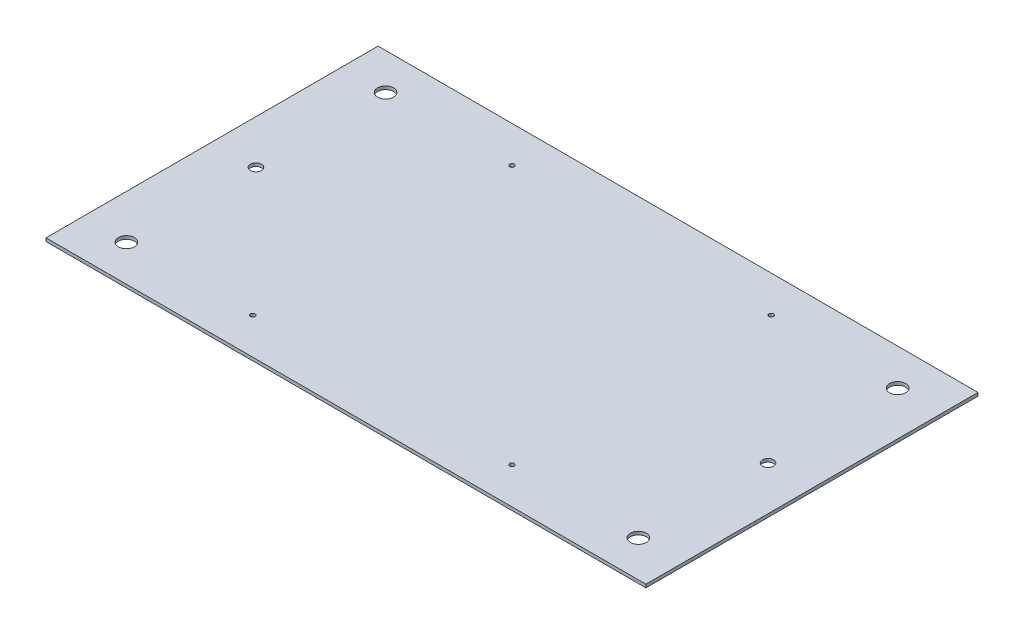
SolidWorks part; units mm, degrees
ref_plane "Front Plane" through (0, 0, 0) normal (0, 0, 1) x (1, 0, 0)
ref_plane "Top Plane" through (0, 0, 0) normal (0, 1, 0) x (1, 0, 0)
ref_plane "Right Plane" through (0, 0, 0) normal (1, 0, 0) x (0, 0, -1)
sketch "Sketch2" plane through (0, 0, 0) normal (0, 1, 0) x (1, 0, 0)
  line L1 (0, 0) -> (560, 0)
  line L2 (0, 0) -> (0, 310)
  line L3 (0, 310) -> (560, 310)
  line L4 (560, 0) -> (560, 310)
  line L5 (0, 0) -> (560, 310) construction
  line L6 (0, 310) -> (560, 0) construction
  point P4 (280, 155)
  dimension "D1" = 310
  dimension "D2" = 560
extrude "Boss-Extrude1" add sketch "Sketch2" along normal blind 3
sketch "Sketch3" plane through (0, 3, 0) normal (0, 1, 0) x (1, 0, 0)
  circle A0 centre (159, 276) radius 2.15
  circle A1 centre (401, 276) radius 2.15
  circle A2 centre (401, 34) radius 2.15
  circle A3 centre (159, 34) radius 2.15
  dimension "D1" = 4.3
  dimension "D2" = 4.3
  dimension "D3" = 4.3
  dimension "D4" = 4.3
extrude "Cut-Extrude1" cut sketch "Sketch3" against normal through all
sketch "Sketch4" plane through (0, 3, 0) normal (0, 1, 0) x (1, 0, 0)
  line L0 (0, 0) -> (560, 0) construction
  circle A0 centre (41, 155) radius 5.15
  circle A1 centre (519, 155) radius 5.15
  circle A2 centre (159, 34) radius 2.15 construction
  circle A3 centre (401, 34) radius 2.15 construction
  dimension "D1" = 118
  dimension "D2" = 118
  dimension "D3" = 155
  dimension "D4" = 155
  dimension "D5" = 10.3
  dimension "D6" = 10.3
extrude "Cut-Extrude2" cut sketch "Sketch4" against normal through all
sketch "Sketch5" plane through (0, 3, 0) normal (0, 1, 0) x (1, 0, 0)
  line L0 (0, 34) -> (560, 34) construction
  line L1 (0, 310) -> (0, 0) construction
  line L2 (560, 0) -> (560, 310) construction
  line L3 (0, 276) -> (560, 276) construction
  line L4 (41, 0) -> (41, 310) construction
  line L5 (560, 310) -> (0, 310) construction
  line L6 (519, 0) -> (519, 310) construction
  circle A0 centre (41, 34) radius 7.5
  circle A4 centre (41, 276) radius 7.5
  circle A5 centre (519, 276) radius 7.5
  circle A6 centre (519, 34) radius 7.5
  point P12 (41, 34)
  point P18 (41, 155)
  point P22 (519, 155)
  point P23 (41, 276)
  point P24 (519, 276)
  point P25 (519, 34)
  dimension "D1" = 15
  dimension "D2" = 15
  dimension "D3" = 15
  dimension "D4" = 15
extrude "Cut-Extrude3" cut sketch "Sketch5" against normal through all
